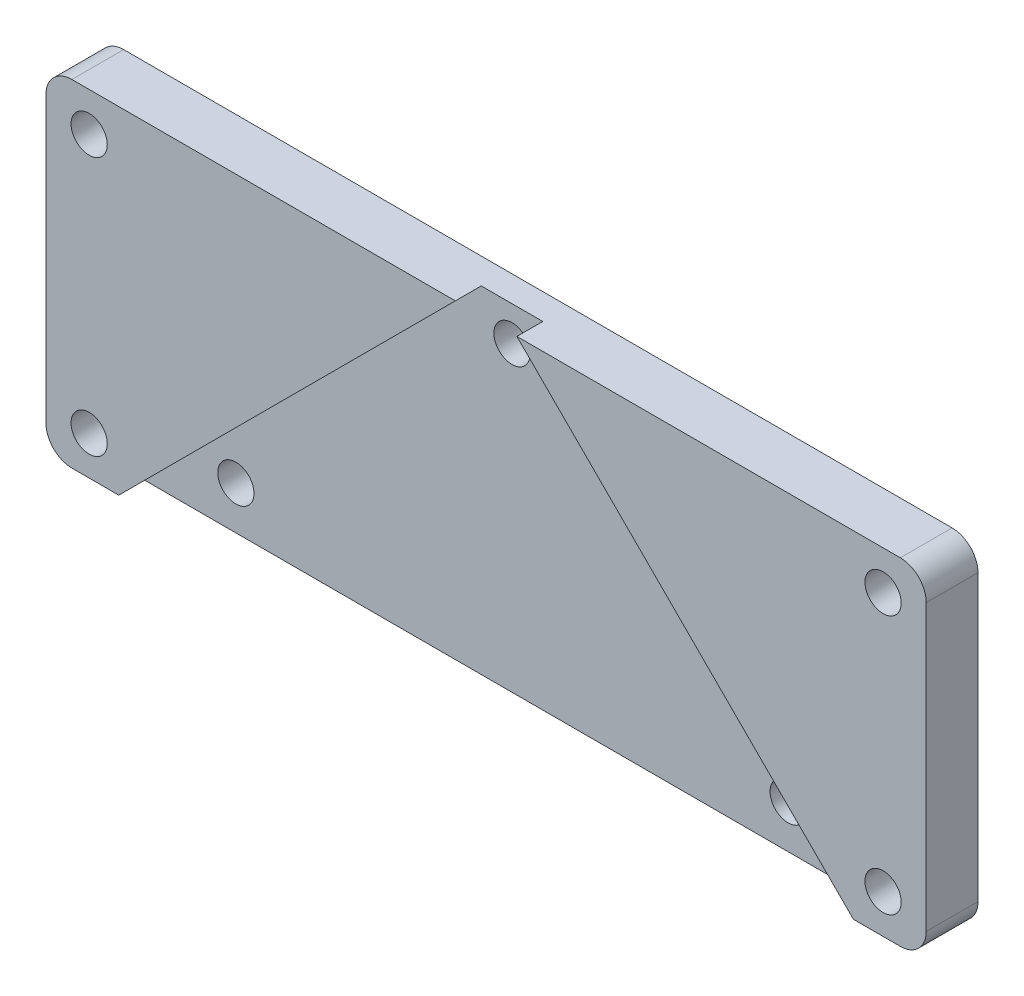
SolidWorks part; units mm, degrees
material "Thornel Mat VMA"
ref_plane "前视基准面" through (0, 0, 0) normal (0, 0, 1) x (1, 0, 0)
ref_plane "上视基准面" through (0, 0, 0) normal (0, 1, 0) x (1, 0, 0)
ref_plane "右视基准面" through (0, 0, 0) normal (1, 0, 0) x (0, 0, -1)
other "Configuration Table"
sketch "草图1" plane through (0, 0, 0) normal (0, 0, 1) x (1, 0, 0)
  line L0 (-32, 0) -> (32, 0) construction
  line L1 (0, 0) -> (0, 30) construction
  line L2 (-42.425, -5) -> (42.425, -5)
  line L3 (-32, -5) -> (32, -5) construction
  line L4 (0, 0) -> (0, -5) construction
  line L5 (-3.425, 34) -> (3.425, 34)
  line L6 (0, 34) -> (0, 30) construction
  line L7 (-3.425, 34) -> (-42.425, -5)
  line L8 (3.425, 34) -> (42.425, -5)
  circle A0 centre (0, 30) radius 2.1
  circle A1 centre (-32, 0) radius 2.1
  circle A2 centre (32, 0) radius 2.1
  point P4 (0, 0)
  point P17 (0, 34)
  dimension "D3" = 4.2
  dimension "D1" = 64
  dimension "D2" = 30
  dimension "D5" = 6.85
  dimension "D6" = 39
  dimension "D7" = 84.85
  dimension "D4" = 5
extrude "凸台-拉伸1" add sketch "草图1" along normal blind 6
sketch "草图2" plane through (0, 0, 6) normal (0, 0, 1) x (1, 0, 0)
  line L0 (-51, -5) -> (51, -5)
  line L1 (-42.425, -5) -> (42.425, -5) construction
  line L2 (3.425, 34) -> (-3.425, 34) construction
  line L3 (3.425, 34) -> (-3.425, 34) construction
  line L4 (-46, -0.5) -> (46, -0.5) construction
  line L5 (-46, -0.5) -> (-46, 29.5) construction
  line L6 (-46, 29.5) -> (46, 29.5) construction
  line L7 (46, -0.5) -> (46, 29.5) construction
  line L8 (-46, -0.5) -> (46, 29.5) construction
  line L9 (-46, 29.5) -> (46, -0.5) construction
  line L11 (-51, -5) -> (-51, 34)
  line L12 (-51, 34) -> (51, 34)
  line L13 (51, -5) -> (51, 34)
  line L14 (-51, -5) -> (51, 34) construction
  line L15 (-51, 34) -> (51, -5) construction
  line L18 (0, 34) -> (0, 14.5) construction
  circle A0 centre (-46, -0.5) radius 2.1
  circle A1 centre (-46, 29.5) radius 2.1
  circle A2 centre (46, 29.5) radius 2.1
  circle A3 centre (46, -0.5) radius 2.1
  circle A4 centre (-32, 0) radius 2.1 construction
  circle A5 centre (0, 30) radius 2.1 construction
  circle A7 centre (32, 0) radius 2.1 construction
  circle A9 centre (-32, 0) radius 2.1
  circle A14 centre (0, 30) radius 2.1
  circle A15 centre (32, 0) radius 2.1
  point P6 (0, 14.5)
  point P15 (0, 14.5)
  dimension "D3" = 4.2
  dimension "D1" = 92
  dimension "D2" = 30
  dimension "D4" = 5
extrude "凸台-拉伸2" add sketch "草图2" against normal up to surface (6 mm away) up to face at (0, 14.5, 0)
sketch "草图3" plane through (0, 0, 6) normal (0, 0, 1) x (1, 0, 0)
  line L0 (3.425, 34) -> (42.425, -5) construction
  line L1 (-3.425, 34) -> (-42.425, -5) construction
  line L2 (3.425, 34) -> (42.425, -5) construction
  line L3 (-3.425, 34) -> (-42.425, -5) construction
  line L4 (-3.5664, 34) -> (-3.425, 34)
  line L5 (-3.5664, 34) -> (-42.4957, -4.9293)
  line L6 (3.5664, 34) -> (42.4957, -4.9293)
  line L7 (51, 34) -> (-51, 34) construction
  line L8 (3.4957, 34.0707) -> (42.4957, -4.9293) construction
  line L9 (-3.4957, 34.0707) -> (-42.4957, -4.9293) construction
  line L11 (-42.4957, -4.9293) -> (-42.5664, -5)
  line L12 (-51, -5) -> (51, -5) construction
  line L13 (-42.5664, -5) -> (-42.425, -5)
  line L14 (3.425, 34) -> (3.5664, 34)
  line L15 (42.4957, -4.9293) -> (42.5664, -5)
  line L16 (42.5664, -5) -> (42.425, -5)
  line L17 (-3.425, 34) -> (3.425, 34)
  line L18 (-42.5664, -5) -> (42.5664, -5)
  circle M1 centre (-32, 0) radius 2.1
  line M2 (51, 34) -> (-51, 34)
  line M4 (-51, -5) -> (51, -5)
  circle M6 centre (0, 30) radius 2.1
  circle M7 centre (32, 0) radius 2.1
  dimension "D1" = 0.1
  dimension "D2" = 0.1
extrude "切除-拉伸2" cut sketch "草图3" against normal offset from surface (3 mm away) 3 contours L15 L6 L5 L11 M2 M4 M1 M6 M7 up to face at (0, 14.5, 0)
fillet "圆角1" radius 3 4 edges at (-51, 34, 3) (-51, -5, 3) (51, 34, 3) (51, -5, 3)
